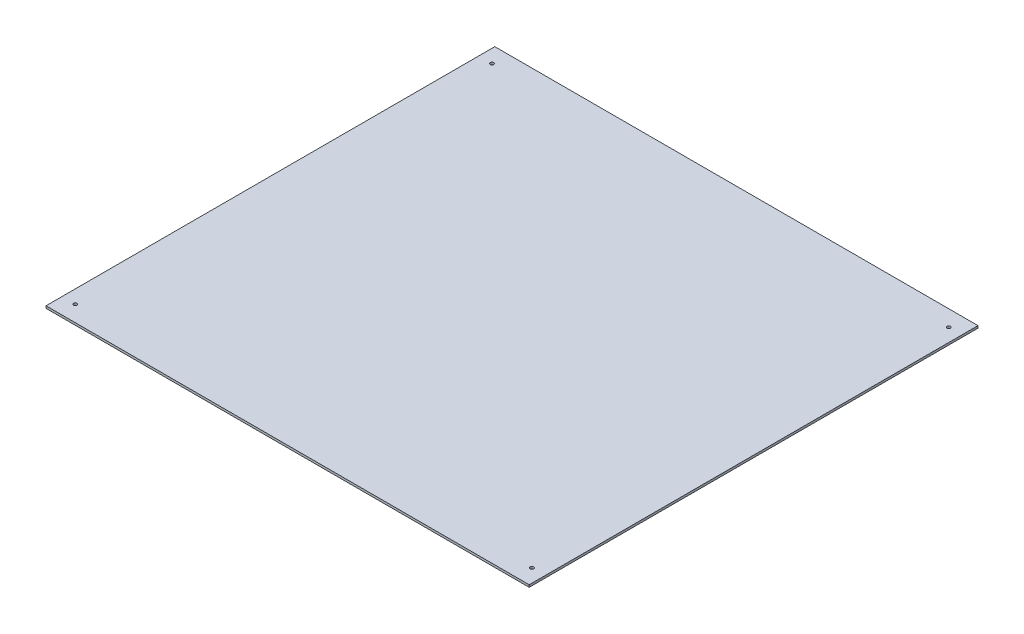
SolidWorks part; units mm, degrees
ref_plane "Alzado" through (0, 0, 0) normal (0, 0, 1) x (1, 0, 0)
ref_plane "Planta" through (0, 0, 0) normal (0, 1, 0) x (1, 0, 0)
ref_plane "Vista lateral" through (0, 0, 0) normal (1, 0, 0) x (0, 0, -1)
sketch "Croquis1" plane through (0, 0, 0) normal (0, 1, 0) x (1, 0, 0)
  line L1 (0, 0) -> (430.5, 0)
  line L2 (0, 0) -> (0, 400)
  line L3 (0, 400) -> (430.5, 400)
  line L4 (430.5, 0) -> (430.5, 400)
  dimension "D1" = 400
  dimension "D2" = 430.5
extrude "Saliente-Extruir1" add sketch "Croquis1" along normal blind 2
sketch "Croquis2" plane through (0, 2, 0) normal (0, 1, 0) x (1, 0, 0)
  line L0 (430.5, 400) -> (0, 400) construction
  line L1 (0, 400) -> (0, 0) construction
  line L2 (215.25, 400) -> (215.25, 0) construction
  line L3 (0, 0) -> (430.5, 0) construction
  line L4 (0, 200) -> (430.5, 200) construction
  line L5 (430.5, 0) -> (430.5, 400) construction
  circle A0 centre (12.5, 385) radius 1.55
  circle A1 centre (418, 385) radius 1.55
  circle A2 centre (418, 15) radius 1.55
  circle A3 centre (12.5, 15) radius 1.55
  dimension "D1" = 3.1
  dimension "D2" = 15
  dimension "D3" = 12.5
extrude "Cortar-Extruir1" cut sketch "Croquis2" against normal up to surface (2 mm away) up to face at (215.25, 0, -200)
sketch "Croquis3" plane through (0, 2, 0) normal (0, 1, 0) x (1, 0, 0)
  line L0 (429.75, 399.25) -> (0.75, 399.25)
  line L1 (0.75, 399.25) -> (0.75, 0.75)
  line L2 (0.75, 0.75) -> (429.75, 0.75)
  line L3 (429.75, 0.75) -> (429.75, 399.25)
  line L4 (0, 400) -> (0, 0)
  line L5 (0, 0) -> (430.5, 0)
  line L6 (430.5, 0) -> (430.5, 400)
  line L7 (430.5, 400) -> (0, 400)
  line L8 (0, 400) -> (0, 0)
  line L9 (0, 0) -> (430.5, 0)
  line L10 (430.5, 0) -> (430.5, 400)
  line L11 (430.5, 400) -> (0, 400)
  dimension "D1" = 0
  dimension "D2" = 0.75
extrude "Cortar-Extruir2" cut sketch "Croquis3" against normal up to surface (2 mm away) up to face at (12.5, 0, -16.55)
